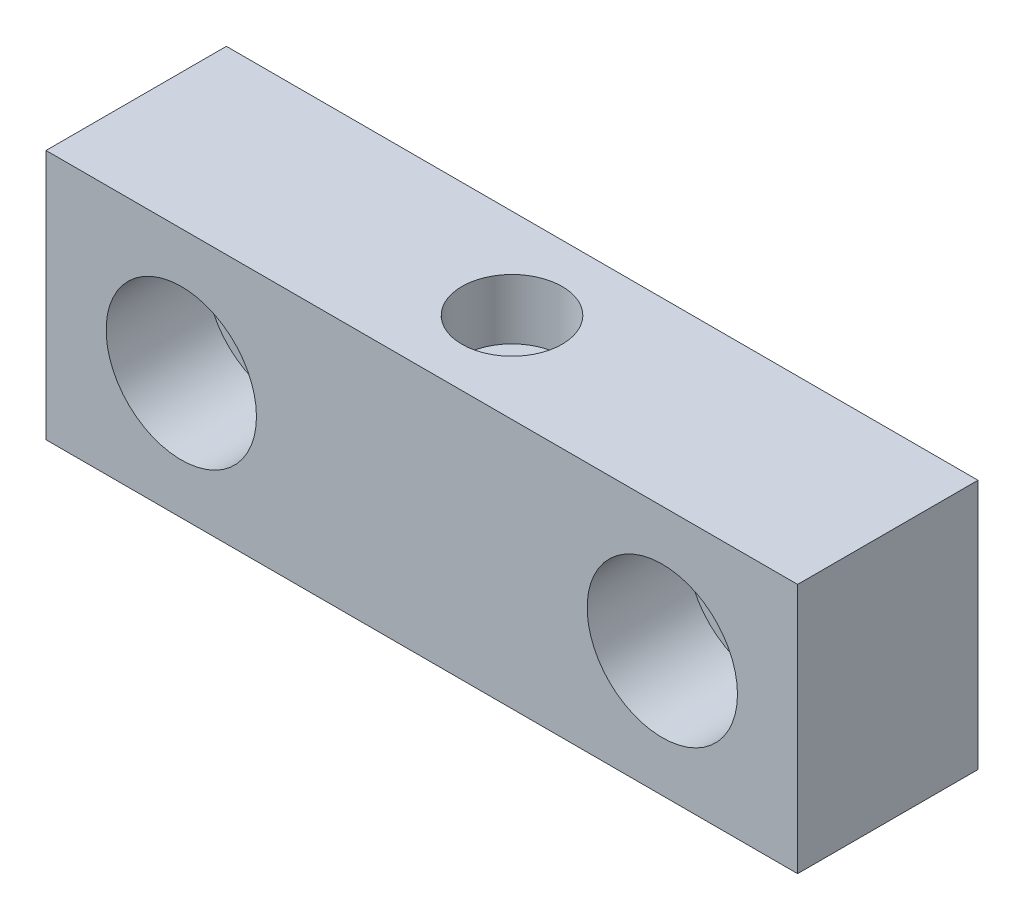
SolidWorks part; units mm, degrees
ref_plane "Front Plane" through (0, 0, 0) normal (0, 0, 1) x (1, 0, 0)
ref_plane "Top Plane" through (0, 0, 0) normal (0, 1, 0) x (1, 0, 0)
ref_plane "Right Plane" through (0, 0, 0) normal (1, 0, 0) x (0, 0, -1)
sketch "Sketch1" plane through (0, 0, 0) normal (0, 0, 1) x (1, 0, 0)
  line L1 (-37.5, -12.5) -> (37.5, -12.5)
  line L2 (-37.5, -12.5) -> (-37.5, 12.5)
  line L3 (-37.5, 12.5) -> (37.5, 12.5)
  line L4 (37.5, -12.5) -> (37.5, 12.5)
  line L5 (-37.5, -12.5) -> (37.5, 12.5) construction
  line L6 (-37.5, 12.5) -> (37.5, -12.5) construction
  point P0 (0, 0)
  dimension "D1" = 75
  dimension "D2" = 25
extrude "Boss-Extrude1" add sketch "Sketch1" along normal blind 18
sketch "Sketch2" plane through (0, 0, 18) normal (0, 0, 1) x (1, 0, 0)
  circle A0 centre (-24, 0) radius 7.5
  circle A1 centre (24, 0) radius 7.5
  dimension "D1" = 15
  dimension "D2" = 15
  dimension "D3" = 48
  dimension "D4" = 24
extrude "Cut-Extrude1" cut sketch "Sketch2" against normal blind 10
sketch "Sketch3" plane through (0, -12.5, 0) normal (0, -1, 0) x (1, 0, 0)
  line L0 (-37.5, 0) -> (37.5, 0) construction
  circle A0 centre (0, 9) radius 2.5
  point P4 (0, 0)
  dimension "D1" = 5
  dimension "D2" = 9
extrude "Cut-Extrude2" cut sketch "Sketch3" against normal through all
sketch "Sketch4" plane through (0, 12.5, 0) normal (0, 1, 0) x (1, 0, 0)
  circle A2 centre (0, -9) radius 5
  circle A3 centre (0, -9) radius 5
  dimension "D1" = 2.5
extrude "Cut-Extrude3" cut sketch "Sketch4" against normal blind 6
